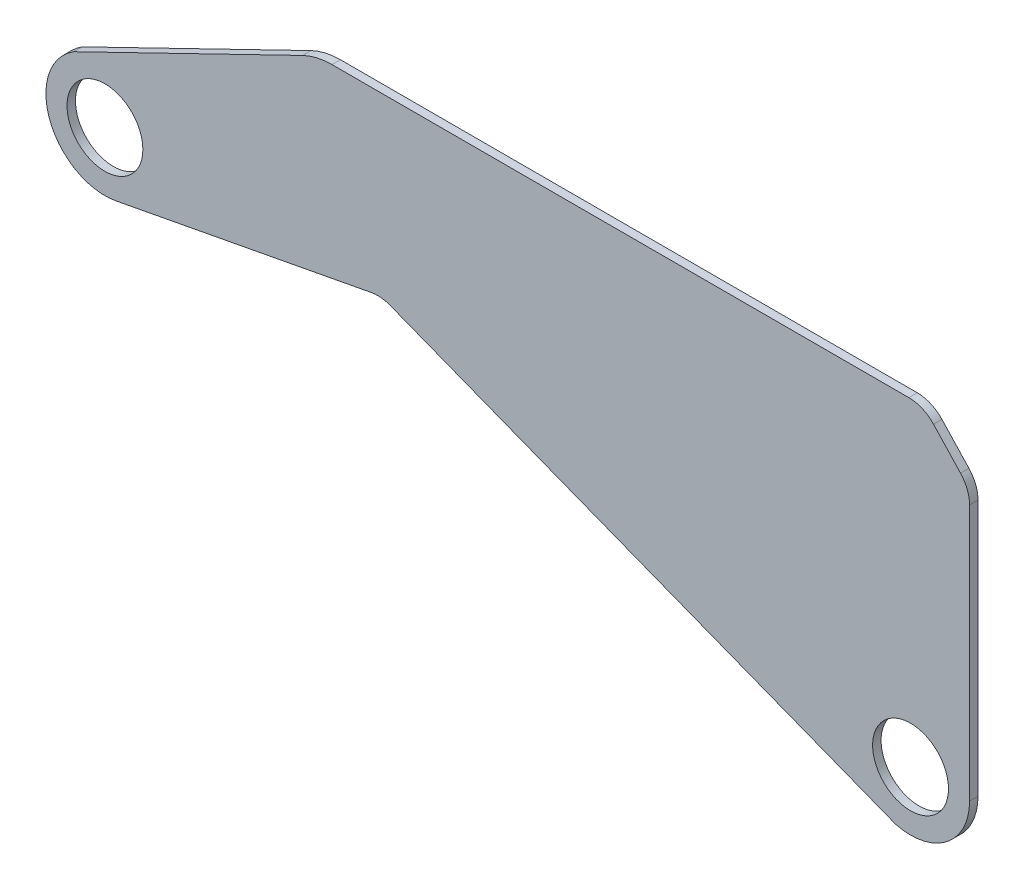
SolidWorks part; units mm, degrees
material "ABS PC"
ref_plane "Front Plane" through (0, 0, 0) normal (0, 0, 1) x (1, 0, 0)
ref_plane "Top Plane" through (0, 0, 0) normal (0, 1, 0) x (1, 0, 0)
ref_plane "Right Plane" through (0, 0, 0) normal (1, 0, 0) x (0, 0, -1)
sketch "Sketch1" plane through (0, 0, 0) normal (0, 0, 1) x (1, 0, 0)
  line L0 (22.225, 0) -> (22.225, 101.6)
  line L1 (22.225, 101.6) -> (4.8791, 120.1548)
  line L2 (4.8791, 120.1548) -> (-223.7209, 120.1548)
  line L3 (-223.7209, 120.1548) -> (-315.1072, 75.7575)
  line L4 (-299.299, 35.0094) -> (-199.4699, 53.8962)
  line L5 (-199.4699, 53.8962) -> (-5.519, -21.5288)
  circle A0 centre (0, 0) radius 14.2875
  arc A1 (-5.519, -21.5288) -> (22.225, 0) centre (0, 0) ccw
  arc A2 (-311.0787, 77.7146) -> (-299.299, 35.0094) centre (-303.4304, 56.8471) ccw
  circle A3 centre (-303.4304, 56.8471) radius 14.2875
  point P3 (-7.6165, -20.9051)
  point P4 (-5.519, -21.5288)
  point P16 (0, 0)
  point P17 (22.2249, 0)
  dimension "D1" = 28.575
  dimension "D2" = 44.45
  dimension "D7" = 44.45
  dimension "D9" = 28.575
  dimension "D3" = 101.6
  dimension "D4" = 25.4
  dimension "D5" = 228.6
  dimension "D6" = 101.6
  dimension "D8" = 101.6
extrude "Boss-Extrude1" add sketch "Sketch1" along normal blind 3.175 contours L3 A2 L4 L5 A1 L0 L1 L2 A3 A0
fillet "Fillet1" radius 12.7 1 edges at (-199.4699, 53.8962, 1.5875)
fillet "Fillet2" radius 25.4 1 edges at (-223.7209, 120.1548, 1.5875)
fillet "Fillet3" radius 12.7 1 edges at (22.225, 101.6, 1.5875)
fillet "Fillet4" radius 12.7 1 edges at (4.8791, 120.1548, 1.5875)
sketch "Sketch2" plane through (0, 0, 3.175) normal (0, 0, 1) x (1, 0, 0)
